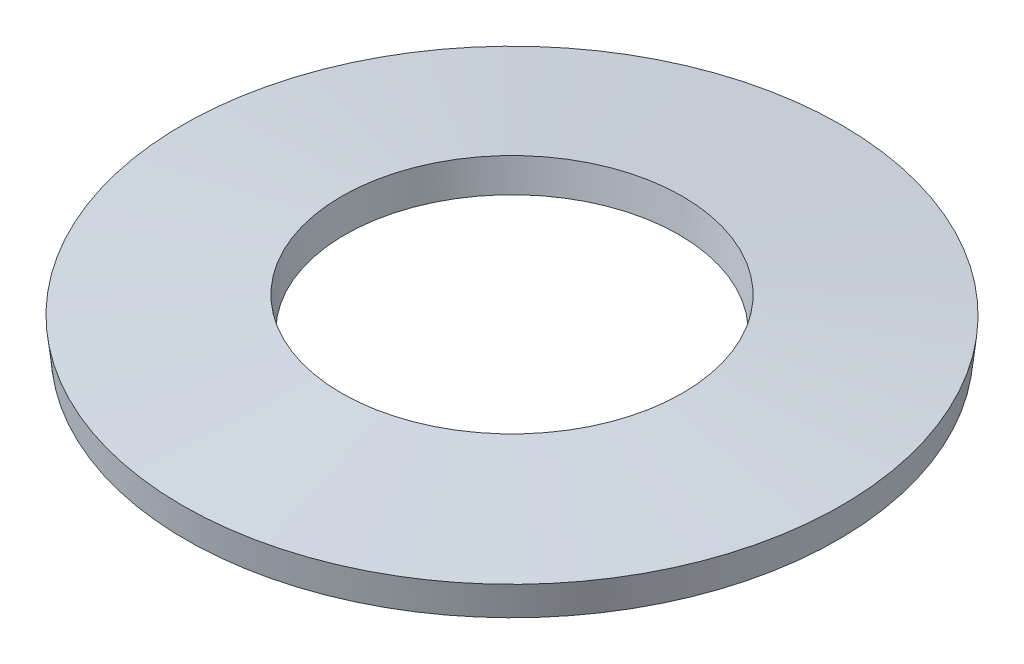
SolidWorks part; units mm, degrees
ref_plane "Front" through (0, 0, 0) normal (0, 0, 1) x (1, 0, 0)
ref_plane "Top" through (0, 0, 0) normal (0, 1, 0) x (1, 0, 0)
ref_plane "Right" through (0, 0, 0) normal (1, 0, 0) x (0, 0, -1)
sketch "Sketch1" plane through (0, 0, 0) normal (0, 0, 1) x (1, 0, 0)
  line L0 (4.7117, 0) -> (2.413, 0.2568)
  line L1 (2.413, 0.2568) -> (2.4638, 0.7112)
  line L2 (2.4638, 0.7112) -> (4.7625, 0.4544)
  line L3 (4.7625, 0.4544) -> (4.7117, 0)
  line L4 (0, 0) -> (0, 0.7112) construction
  dimension "ID" = 4.826
  dimension "OD" = 9.525
  dimension "Thickness" = 0.4572
  dimension "Height" = 0.7112
revolve "Revolve1" add sketch "Sketch1" angle 360 about L4
